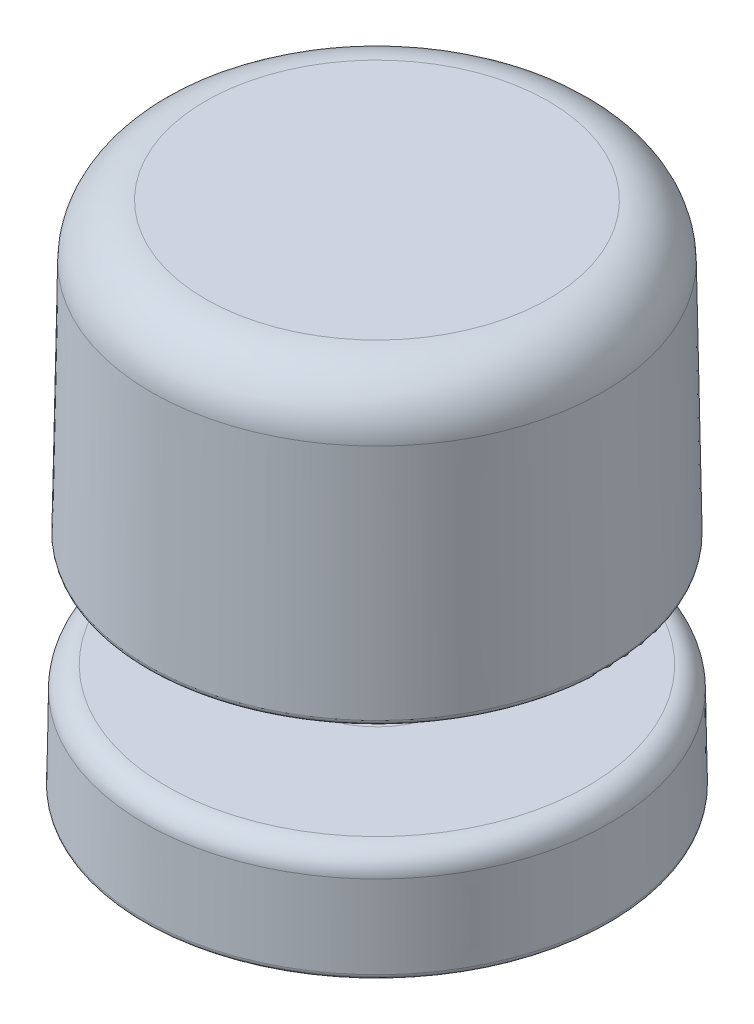
SolidWorks part; units mm, degrees
ref_plane "Front Plane" through (0, 0, 0) normal (0, 0, 1) x (1, 0, 0)
ref_plane "Top Plane" through (0, 0, 0) normal (0, 1, 0) x (1, 0, 0)
ref_plane "Right Plane" through (0, 0, 0) normal (1, 0, 0) x (0, 0, -1)
sketch "Sketch1" plane through (0, 0, 0) normal (0, 0, 1) x (1, 0, 0)
  line L0 (0, 0) -> (0, 36020.5427) construction
  line L1 (0, 47) -> (15.7661, 47)
  line L2 (20.7654, 42.0873) -> (21.142, 20.5087)
  line L3 (20.6421, 20) -> (7, 20)
  line L4 (5, 18) -> (5, 12)
  line L5 (7, 10) -> (19.3601, 10)
  line L6 (21.3598, 8.0349) -> (21.4911, 0.5087)
  line L7 (20.9912, 0) -> (0, 0)
  line L8 (0, 47) -> (0, 0)
  arc A0 (15.7661, 47) -> (20.7654, 42.0873) centre (15.7661, 42) cw
  arc A1 (19.3601, 10) -> (21.3598, 8.0349) centre (19.3601, 8) cw
  arc A2 (5, 12) -> (7, 10) centre (7, 12) ccw
  arc A3 (7, 20) -> (5, 18) centre (7, 18) ccw
  arc A4 (21.4911, 0.5087) -> (20.9912, 0) centre (20.9912, 0.5) cw
  arc A5 (21.142, 20.5087) -> (20.6421, 20) centre (20.6421, 20.5) cw
  point P15 (21.146, 24.8711)
  point P16 (0, 0)
  point P17 (20.6982, 24.8204)
  point P20 (5, 10)
  point P23 (5, 20)
  point P26 (21.5, 0)
  point P29 (21.1509, 20)
  dimension "D2" = 2
  dimension "D7" = 5
  dimension "D9" = 2
  dimension "D10" = 2
  dimension "D11" = 0.5
  dimension "D1" = 21.5
  dimension "D3" = 47
  dimension "D4" = 10
  dimension "D5" = 10
  dimension "D6" = 89
  dimension "D8" = 5
revolve "Revolve1" add sketch "Sketch1" angle 360 about L0
hole_wizard "1/4 (0.25) Diameter Hole1" positions "Sketch5" profile "Sketch4" hole size "1/4" standard "ANSI Inch"
sketch "Sketch5" plane through (0, 0, 0) normal (0, -1, 0) x (-1, 0, 0)
  point P0 (0, 0)
sketch "Sketch4" plane through (0, 0, 0) normal (1, 0, 0) x (0, 0, -1)
  line L0 (0, 0) -> (0, 11.9077)
  line L1 (0, 11.9077) -> (3.175, 10)
  line L2 (3.175, 10) -> (3.175, 0)
  line L5 (3.175, 0) -> (0, 0)
  line L10 (0, 11.9077) -> (-3.175, 10) construction
  line L11 (0, -6.35) -> (0, 107.95) construction
  dimension "Hole Dia." = 6.35
  dimension "Hole Depth" = 10
  dimension "Drill Angle" = 118
